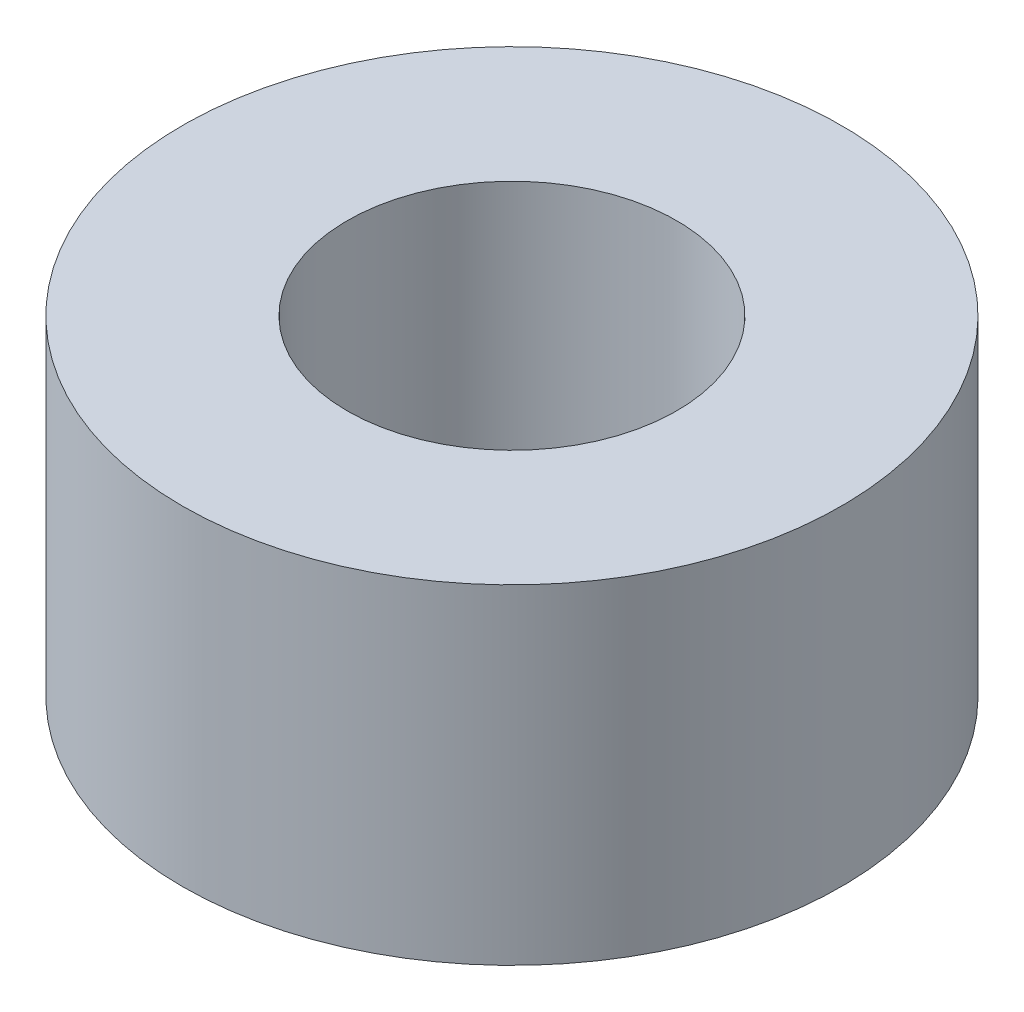
SolidWorks part; units mm, degrees
ref_plane "Front" through (0, 0, 0) normal (0, 0, 1) x (1, 0, 0)
ref_plane "Top" through (0, 0, 0) normal (0, 1, 0) x (1, 0, 0)
ref_plane "Right" through (0, 0, 0) normal (1, 0, 0) x (0, 0, -1)
sketch "Sketch1" plane through (0, 0, 0) normal (0, 1, 0) x (1, 0, 0)
  circle A0 centre (0, 0) radius 6.35
  circle A1 centre (0, 0) radius 3.175
  dimension "OD" = 12.7
  dimension "ID" = 6.35
extrude "Thickness" add sketch "Sketch1" along normal blind 6.35
